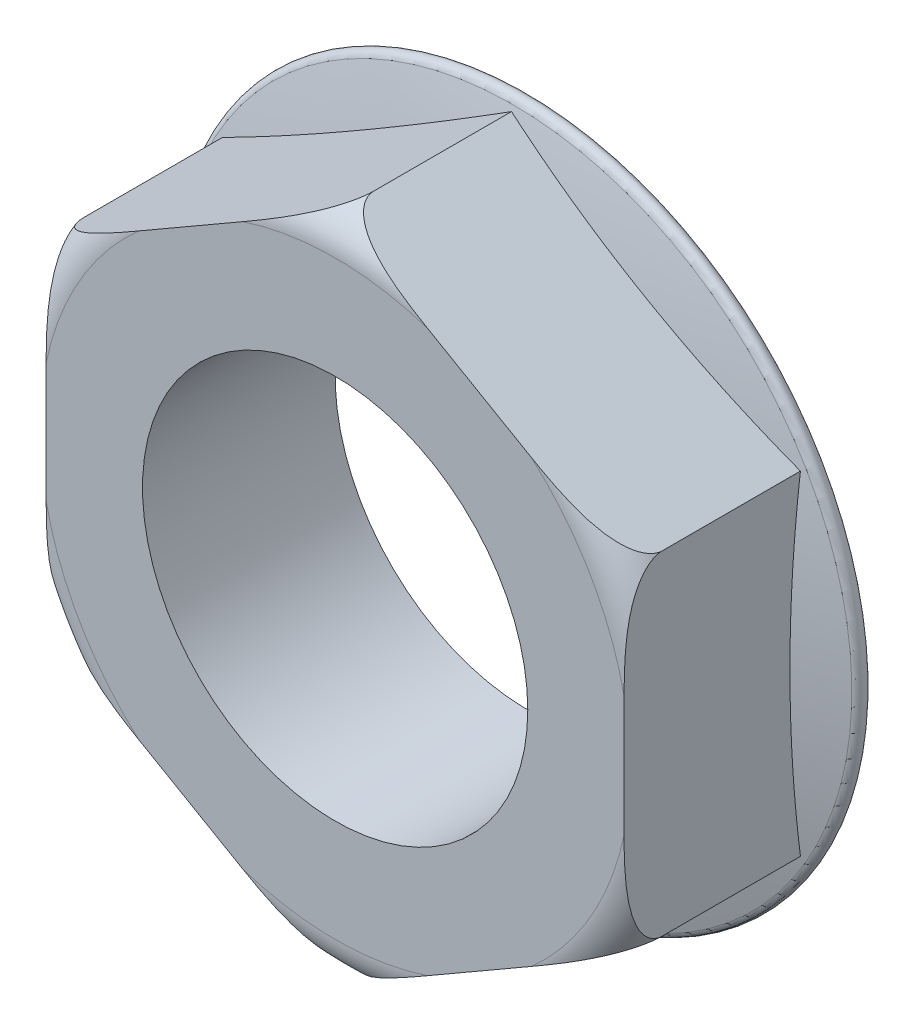
SolidWorks part; units mm, degrees
ref_plane "Plane1" through (0, 0, 0) normal (0, 0, 1) x (1, 0, 0)
ref_plane "Plane2" through (0, 0, 0) normal (0, 1, 0) x (-1, 0, 0)
ref_plane "Plane3" through (0, 0, 0) normal (1, 0, 0) x (0, 0, -1)
other "Configuration Table"
sketch "Head Sketch" plane through (0, 0, 0) normal (0, 0, 1) x (1, 0, 0)
  line L0 (0, 21.997) -> (19.05, 10.9985)
  line L1 (19.05, 10.9985) -> (19.05, -10.9985)
  line L2 (19.05, -10.9985) -> (0, -21.997)
  line L3 (0, -21.997) -> (-19.05, -10.9985)
  line L4 (-19.05, -10.9985) -> (-19.05, 10.9985)
  line L5 (-19.05, 10.9985) -> (0, 21.997)
  line L6 (19.05, 10.9985) -> (-19.05, -10.9985) construction
  line L7 (0, 21.997) -> (0, -21.997) construction
  line L8 (-19.05, 10.9985) -> (19.05, -10.9985) construction
  point P0 (0, 0)
  dimension "D1" = 60
  dimension "D2" = 60
  dimension "Flats" = 38.1
extrude "Head" add sketch "Head Sketch" along normal blind 12.7
sketch "Flange Sketch" plane through (0, 0, 0) normal (0, 1, 0) x (-1, 0, 0)
  line L0 (0, 1.8434) -> (0, 3.81) construction
  line L1 (-22.225, 0) -> (0, 0)
  line L2 (0, 50) -> (0, -50) construction
  line L4 (0, 0) -> (0, 3.81)
  line L5 (0, 0) -> (-19.05, 0) construction
  arc A0 (0, 3.81) -> (-22.3494, 0.9843) centre (0, -85.9866) ccw
  arc A1 (-22.225, 0) -> (-22.3494, 0.9843) centre (-22.225, 0.5) cw
  dimension "D1" = 0.5
  dimension "D3" = 44.45
  dimension "Flange Height" = 3.81
revolve "Flange" add sketch "Flange Sketch" angle 360 about L0
sketch "Sketch5" plane through (0, 0, 0) normal (1, 0, 0) x (0, 0, -1)
  line L0 (-12.7, -19.457) -> (-12.7, -21.997)
  line L1 (-12.7, -21.997) -> (-10.16, -21.997)
  line L2 (-12.7, -21.997) -> (-1.0741, -21.997) construction
  line L3 (-12.7, -21.997) -> (-12.7, -10.9985) construction
  line L5 (-15.0856, 0) -> (-8.1394, 0) construction
  line L6 (50, 0) -> (-50, 0) construction
  arc A0 (-12.7, -19.457) -> (-10.16, -21.997) centre (-10.16, -19.457) ccw
  dimension "D1" = 2.54
revolve "Head Trim" cut sketch "Sketch5" angle 360 about L5
sketch "Hole Sketch" plane through (0, 0, 12.7) normal (0, 0, 1) x (1, 0, 0)
  line L0 (50, 0) -> (-50, 0) construction
  line L1 (0, -50) -> (0, 50) construction
  circle A0 centre (0, 0) radius 12.7
  dimension "Hole Dia" = 25.4
extrude "Through Hole" cut sketch "Hole Sketch" against normal through all
cosmetic thread "Cosmetic Thread1" parameters "D2"=9
